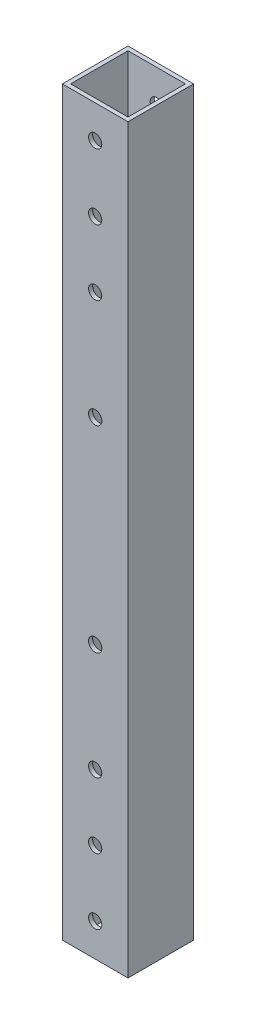
SolidWorks part; units mm, degrees
material "6061 Alloy"
ref_plane "Front" through (0, 0, 0) normal (0, 0, 1) x (1, 0, 0)
ref_plane "Top" through (0, 0, 0) normal (0, 1, 0) x (1, 0, 0)
ref_plane "Right" through (0, 0, 0) normal (1, 0, 0) x (0, 0, -1)
sketch "Sketch1" plane through (0, 0, 0) normal (0, 1, 0) x (1, 0, 0)
  line L1 (-11.1125, 11.1125) -> (11.1125, 11.1125)
  line L2 (-11.1125, 11.1125) -> (-11.1125, -11.1125)
  line L3 (-11.1125, -11.1125) -> (11.1125, -11.1125)
  line L4 (11.1125, 11.1125) -> (11.1125, -11.1125)
  line L5 (-11.1125, 11.1125) -> (11.1125, -11.1125) construction
  line L6 (-11.1125, -11.1125) -> (11.1125, 11.1125) construction
  line L7 (-12.7, 12.7) -> (12.7, 12.7)
  line L8 (-12.7, 12.7) -> (-12.7, -12.7)
  line L9 (-12.7, -12.7) -> (12.7, -12.7)
  line L10 (12.7, 12.7) -> (12.7, -12.7)
  line L11 (-12.7, 12.7) -> (12.7, -12.7) construction
  line L12 (-12.7, -12.7) -> (12.7, 12.7) construction
  point P0 (0, 0)
  point P6 (0, 0)
  dimension "D1" = 1.5875
  dimension "D2" = 1.5875
  dimension "D3" = 25.4
  dimension "D4" = 25.4
extrude "Boss-Extrude1" add sketch "Sketch1" along normal blind 287.02
hole_wizard "#10 Clearance Hole1" positions "Sketch4" profile "Sketch5" hole size "#10" standard "ANSI Inch" end condition through all
sketch "Sketch4" plane through (0, 0, 12.7) normal (0, 0, 1) x (1, 0, 0)
  point P0 (0, 274.32)
  point P3 (0, 248.92)
  point P6 (0, 223.52)
  point P9 (0, 63.5)
  point P12 (0, 38.1)
  point P15 (0, 12.7)
sketch "Sketch5" plane through (0, 274.32, 12.7) normal (1, 0, 0) x (0, -1, 0)
  line L0 (0, 0) -> (0, 25.4)
  line L1 (0, 25.4) -> (2.5527, 25.4)
  line L2 (2.5527, 25.4) -> (2.5527, 0)
  line L5 (2.5527, 0) -> (0, 0)
  line L11 (0, -6.35) -> (0, 107.95) construction
  dimension "Thru Hole Dia." = 5.1054
  dimension "Thru Hole Depth" = 25.4
hole_wizard "13/64 (0.20313) Diameter Hole1" positions "Sketch6" profile "Sketch7" hole size "13/64" standard "ANSI Inch" end condition through all
sketch "Sketch6" plane through (-522.1702, -199.39, -12.7) normal (0, 0, -1) x (0, 1, 0)
  line L6 (304.8, 522.1702) -> (381, 522.1702) construction
  line L7 (342.9, 509.4702) -> (342.9, 522.1702) construction
  line L8 (342.9, 522.1702) -> (342.9, 534.8702) construction
  line L10 (486.41, 534.8702) -> (199.39, 534.8702) construction
  line L11 (486.41, 509.4702) -> (199.39, 509.4702) construction
  point P18 (304.8, 522.1702)
  point P20 (381, 522.1702)
  point P32 (342.9, 534.8702)
  point P39 (342.9, 509.4702)
  dimension "D1" = 76.2
sketch "Sketch7" plane through (0, 105.41, -12.7) normal (1, 0, 0) x (0, 1, 0)
  line L0 (0, 0) -> (0, 25.4)
  line L1 (0, 25.4) -> (2.5798, 25.4)
  line L2 (2.5798, 25.4) -> (2.5798, 0)
  line L3 (2.5798, 0) -> (0, 0)
  line L4 (0, -6.35) -> (0, 107.95) construction
  dimension "Thru Hole Dia." = 5.1595
  dimension "Thru Hole Depth" = 25.4
